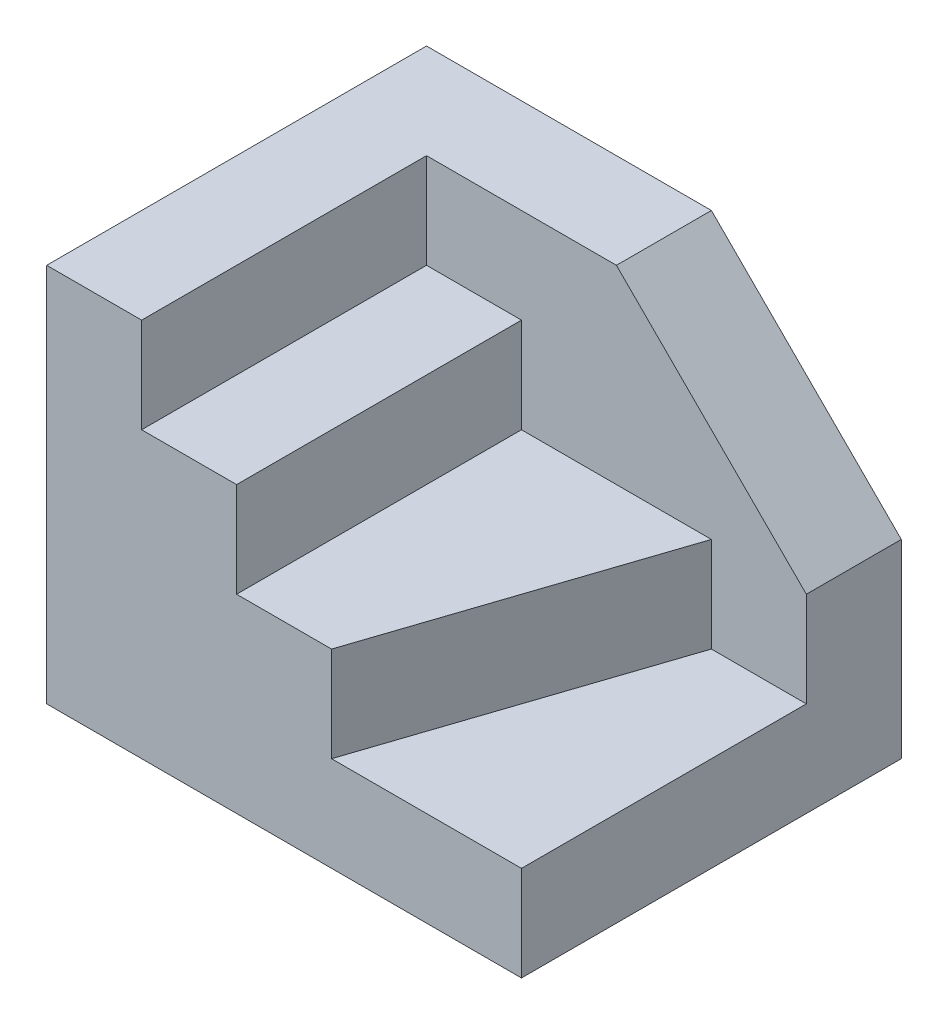
SolidWorks part; units mm, degrees
ref_plane "前基準面" through (0, 0, 0) normal (0, 0, 1) x (1, 0, 0)
ref_plane "上基準面" through (0, 0, 0) normal (0, 1, 0) x (1, 0, 0)
ref_plane "右基準面" through (0, 0, 0) normal (1, 0, 0) x (0, 0, -1)
sketch "草圖1" plane through (0, 0, 0) normal (0, 1, 0) x (1, 0, 0)
  line L0 (0, 0) -> (0, 4)
  line L1 (0, 4) -> (5, 4)
  line L2 (5, 4) -> (5, 0)
  line L3 (5, 0) -> (0, 0)
  dimension "D1" = 4
  dimension "D2" = 5
extrude "填料-伸長1" add sketch "草圖1" along normal blind 1
sketch "草圖2" plane through (0, 0, -4) normal (0, 0, -1) x (-1, 0, 0)
  line L0 (0, 1) -> (0, 4)
  line L1 (0, 4) -> (-3, 4)
  line L2 (-3, 4) -> (-5, 2)
  line L3 (-5, 2) -> (-5, 1)
  line L4 (-5, 1) -> (0, 1)
  dimension "D1" = 3
  dimension "D2" = 3
  dimension "D3" = 1
extrude "填料-伸長2" add sketch "草圖2" against normal blind 1
sketch "草圖3" plane through (0, 0, 0) normal (0, 0, 1) x (1, 0, 0)
  line L0 (0, 1) -> (0, 4)
  line L1 (0, 1) -> (0, 0) construction
  line L2 (0, 1) -> (5, 1) construction
  line L3 (0, 4) -> (1, 4)
  line L4 (0, 4) -> (3, 4) construction
  line L5 (1, 4) -> (1, 3)
  line L6 (1, 3) -> (2, 3)
  line L7 (2, 3) -> (2, 2)
  line L8 (2, 2) -> (3, 2)
  line L9 (3, 2) -> (3, 1)
  line L10 (3, 1) -> (0, 1)
  dimension "D1" = 1
  dimension "D2" = 1
  dimension "D3" = 1
  dimension "D4" = 1
  dimension "D5" = 1
extrude "填料-伸長3" add sketch "草圖3" against normal blind 3
sketch "草圖4" plane through (0, 1, 0) normal (0, 1, 0) x (1, 0, 0)
  line L0 (3, 0) -> (3, 3)
  line L1 (3, 3) -> (4, 3)
  line L2 (5, 3) -> (3, 3) construction
  line L3 (4, 3) -> (3, 0)
extrude "填料-伸長4" add sketch "草圖4" along normal blind 1
